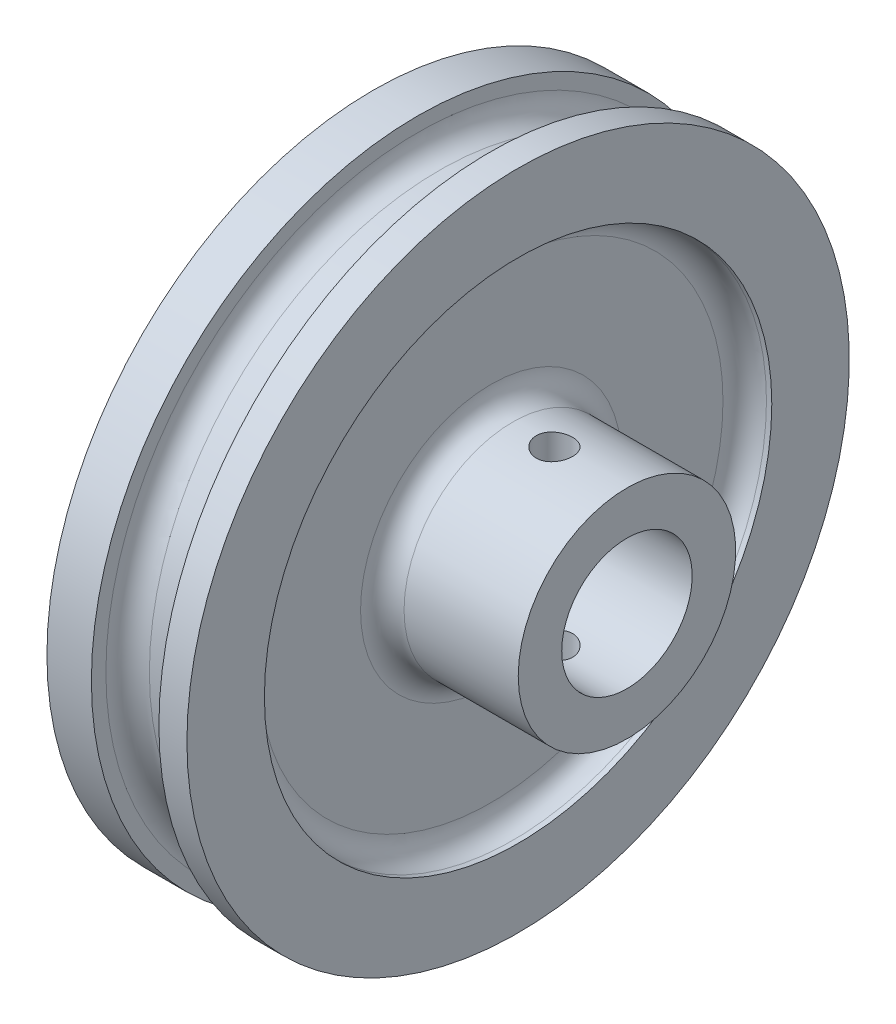
SolidWorks part; units mm, degrees
ref_plane "Front Plane" through (0, 0, 0) normal (0, 0, 1) x (1, 0, 0)
ref_plane "Top Plane" through (0, 0, 0) normal (0, 1, 0) x (1, 0, 0)
ref_plane "Right Plane" through (0, 0, 0) normal (1, 0, 0) x (0, 0, -1)
sketch "Sketch1" plane through (0, 0, 0) normal (0, 0, 1) x (1, 0, 0)
  line L0 (-27.299, 0) -> (32.8247, 0) construction
  line L1 (-13.6376, 9) -> (21.3798, 9)
  line L2 (21.3798, 9) -> (21.3798, 15)
  line L3 (21.3798, 15) -> (5.6272, 15)
  line L4 (2.6272, 18) -> (2.6272, 32)
  line L5 (5.6272, 35) -> (6.3624, 35)
  line L6 (6.3624, 35) -> (6.3624, 45.6877)
  line L7 (6.3624, 45.6877) -> (2.4948, 45.6877)
  line L8 (2.4948, 45.6877) -> (2.4948, 43)
  line L9 (-0.5052, 40) -> (-4.5052, 40)
  line L10 (-7.5052, 43) -> (-7.5052, 45)
  line L11 (-7.5052, 45) -> (-13.6376, 45)
  line L12 (-13.6376, 45) -> (-13.6376, 9)
  arc A0 (2.6272, 32) -> (5.6272, 35) centre (5.6272, 32) cw
  arc A1 (5.6272, 15) -> (2.6272, 18) centre (5.6272, 18) cw
  arc A2 (2.4948, 43) -> (-0.5052, 40) centre (-0.5052, 43) cw
  arc A3 (-4.5052, 40) -> (-7.5052, 43) centre (-4.5052, 43) cw
  point P21 (2.4948, 40)
  point P24 (-7.5052, 40)
  dimension "D8" = 3
  dimension "D1" = 20
  dimension "D2" = 10
  dimension "D3" = 90
  dimension "D4" = 80
  dimension "D5" = 18
  dimension "D6" = 30
  dimension "D7" = 70
revolve "Revolve2" add sketch "Sketch1" angle 360 about L0
ref_plane "Plane1" through (0, 15, 0) normal (0, 1, 0) x (1, 0, 0)
sketch "Sketch2" plane through (0, 15, 0) normal (0, 1, 0) x (1, 0, 0)
  line L0 (21.3798, -15) -> (21.3798, 15) construction
  circle A0 centre (11.3798, 0) radius 2.5
  dimension "D1" = 10
extrude "Cut-Extrude1" cut sketch "Sketch2" against normal through all
